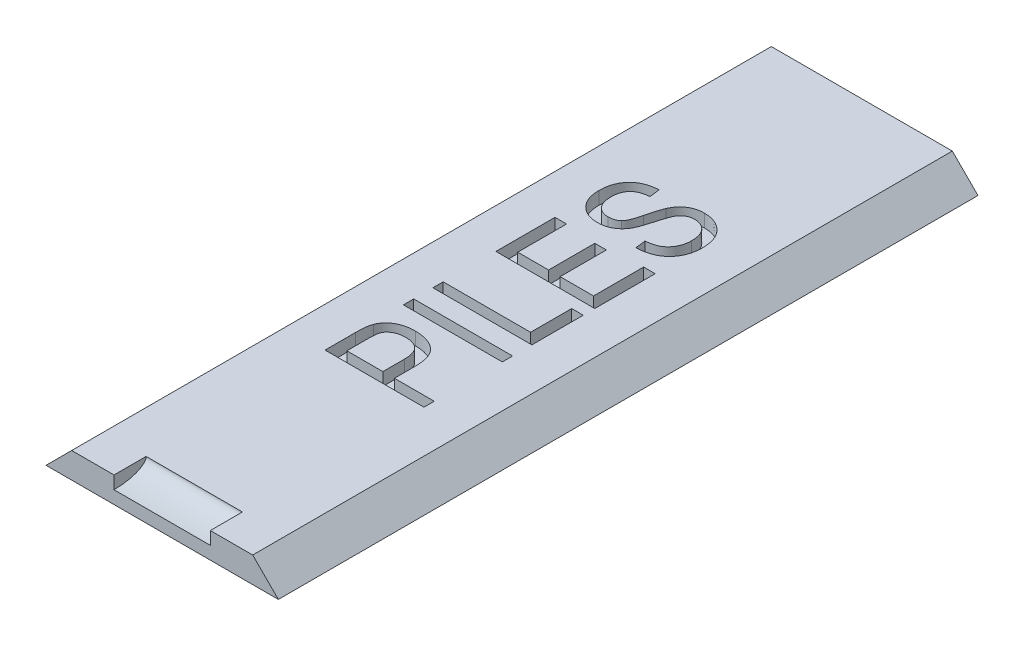
SolidWorks part; units mm, degrees
ref_plane "Alzado" through (0, 0, 0) normal (0, 0, 1) x (1, 0, 0)
ref_plane "Planta" through (0, 0, 0) normal (0, 1, 0) x (1, 0, 0)
ref_plane "Vista lateral" through (0, 0, 0) normal (1, 0, 0) x (0, 0, -1)
sketch "Croquis1" plane through (0, 0, 0) normal (0, 0, 1) x (1, 0, 0)
  line L0 (0, 0) -> (2, 2)
  line L1 (0, 0) -> (18.1, 0)
  line L2 (16.1, 2) -> (18.1, 0)
  line L3 (16.1, 2) -> (2, 2)
  dimension "D1" = 2
  dimension "D2" = 45
  dimension "D3" = 18.1
  dimension "D4" = 45
extrude "Saliente-Extruir1" add sketch "Croquis1" along normal blind 54.5
ref_plane "Plano1" through (9.05, 0, 0) normal (1, 0, 0) x (0, 0, -1)
sketch "Croquis3" plane through (9.05, 0, 0) normal (1, 0, 0) x (0, 0, -1)
  line L2 (-54.5, 2) -> (0, 2) construction
  line L3 (-54.5, 0) -> (-54.5, 2) construction
  ellipse E0 centre (-54.5, 2) end of major axis (-52, 2) minor radius 1
  dimension "D1" = 2.5
  dimension "D2" = 1
extrude "Cortar-Extruir2" cut sketch "Croquis3" against normal mid plane 7.5
sketch "Croquis4" plane through (0, 2, 0) normal (0, 1, 0) x (1, 0, 0)
  line L0 (12.8, -52) -> (12.8, 0) construction
  line L1 (16.1, 0) -> (2, 0) construction
  text T0 "PILES" font "Arial Narrow" height in points 30
extrude "Cortar-Extruir3" cut sketch "Croquis4" against normal blind 1
